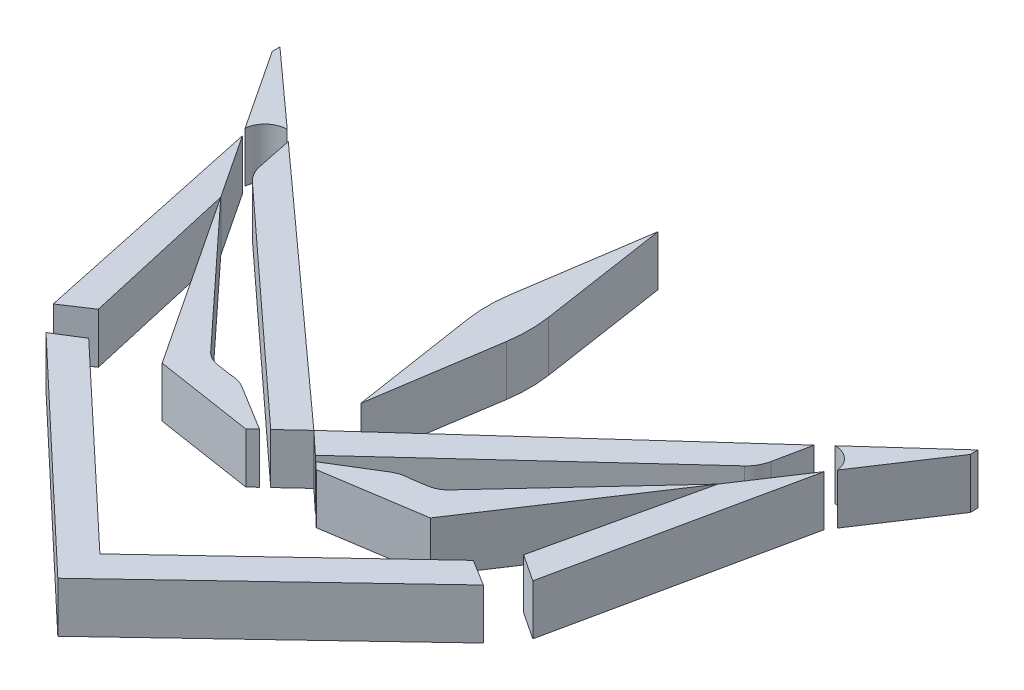
SolidWorks part; units mm, degrees
ref_plane "Front Plane" through (0, 0, 0) normal (0, 0, 1) x (1, 0, 0)
ref_plane "Top Plane" through (0, 0, 0) normal (0, 1, 0) x (1, 0, 0)
ref_plane "Right Plane" through (0, 0, 0) normal (1, 0, 0) x (0, 0, -1)
sketch "Sketch1" plane through (0, 0, 0) normal (0, 1, 0) x (1, 0, 0)
  line L0 (-34.3583, 111.2023) -> (-103.7706, 173.8654)
  line L1 (-103.7706, 173.8654) -> (-103.7706, 172.3321)
  line L2 (-103.7706, 172.3321) -> (-61.0199, 107.7002)
  line L3 (-61.0199, 107.7002) -> (-41.3657, 104.6718)
  line L4 (-41.3657, 104.6718) -> (-34.3583, 111.2023)
  line L5 (-92.2023, 154.8429) -> (-82.0422, 107.0612)
  line L6 (-82.0422, 107.0612) -> (-76.6482, 110.629)
  line L7 (-76.6482, 110.629) -> (-83.7755, 142.103)
  line L8 (-34.3583, 60.2804) -> (-34.3583, 179.6239) construction
  line L9 (-37.1322, 103.8965) -> (-40.9001, 104.4454)
  line L10 (-42.25, 103.8965) -> (-43.2539, 102.5863)
  line L11 (-72.6076, 104.6718) -> (-77.8414, 101.4158)
  line L12 (-77.8414, 101.4158) -> (-34.3583, 60.2804)
  line L13 (-34.3583, 68.6493) -> (-72.6076, 104.6718)
  line L14 (-39.9543, 105.9871) -> (-48.9893, 111.5383)
  line L15 (-52.3282, 112.482) -> (-55.26, 112.9474)
  line L16 (-57.9726, 114.2861) -> (-83.7755, 142.103)
  line L18 (-86.6454, 158.4053) -> (-85.1748, 151.2715)
  line L19 (-83.2991, 147.9149) -> (-38.8018, 107.0612)
  line L20 (-34.3583, 179.6239) -> (-38.2146, 154.0307)
  line L21 (-38.2035, 145.657) -> (-34.3583, 120.5907)
  line L22 (-34.3583, 120.5907) -> (-34.3583, 179.6239)
  line L23 (-43.2539, 102.5863) -> (-37.1322, 103.3967)
  line L24 (-37.1322, 103.3967) -> (-37.1322, 103.8965)
  line L25 (-31.5845, 103.3967) -> (-31.5845, 103.8965)
  line L26 (-25.4628, 102.5863) -> (-31.5845, 103.3967)
  line L27 (-30.5132, 145.657) -> (-34.3583, 120.5907)
  line L28 (-34.3583, 179.6239) -> (-30.502, 154.0307)
  line L29 (14.5824, 147.9149) -> (-29.9148, 107.0612)
  line L30 (17.9287, 158.4053) -> (16.4582, 151.2715)
  line L32 (-10.7441, 114.2861) -> (15.0589, 142.103)
  line L33 (-16.3885, 112.482) -> (-13.4567, 112.9474)
  line L34 (-28.7623, 105.9871) -> (-19.7273, 111.5383)
  line L35 (-34.3583, 68.6493) -> (3.891, 104.6718)
  line L36 (9.1248, 101.4158) -> (-34.3583, 60.2804)
  line L37 (3.891, 104.6718) -> (9.1248, 101.4158)
  line L38 (-26.4666, 103.8965) -> (-25.4628, 102.5863)
  line L39 (-31.5845, 103.8965) -> (-27.8165, 104.4454)
  line L40 (7.9315, 110.629) -> (15.0589, 142.103)
  line L41 (13.3255, 107.0612) -> (7.9315, 110.629)
  line L42 (23.4857, 154.8429) -> (13.3255, 107.0612)
  line L43 (-27.3509, 104.6718) -> (-34.3583, 111.2023)
  line L44 (-7.6968, 107.7002) -> (-27.3509, 104.6718)
  line L45 (35.0539, 172.3321) -> (-7.6968, 107.7002)
  line L46 (35.0539, 173.8654) -> (35.0539, 172.3321)
  line L47 (-34.3583, 111.2023) -> (35.0539, 173.8654)
  arc A0 (-48.9893, 111.5383) -> (-52.3282, 112.482) centre (-52.3282, 106.104) ccw
  arc A1 (-55.26, 112.9474) -> (-57.9726, 114.2861) centre (-54.4603, 117.9855) cw
  arc A2 (-85.1748, 151.2715) -> (-83.2991, 147.9149) centre (-78.9301, 152.5588) ccw
  arc A3 (-88.849, 160.3947) -> (-93.2599, 156.4417) centre (-88.841, 155.9483) ccw
  arc A4 (-38.2146, 154.0307) -> (-38.2035, 145.657) centre (-10.6707, 149.8805) ccw
  arc A5 (-40.9001, 104.4454) -> (-42.25, 103.8965) centre (-41.1076, 103.0211) ccw
  arc A6 (-27.8165, 104.4454) -> (-26.4666, 103.8965) centre (-27.6091, 103.0211) cw
  arc A7 (-30.502, 154.0307) -> (-30.5132, 145.657) centre (-58.0459, 149.8805) cw
  arc A8 (20.1324, 160.3947) -> (24.5432, 156.4417) centre (20.1243, 155.9483) cw
  arc A9 (16.4582, 151.2715) -> (14.5824, 147.9149) centre (10.2135, 152.5588) cw
  arc A10 (-13.4567, 112.9474) -> (-10.7441, 114.2861) centre (-14.2564, 117.9855) ccw
  arc A11 (-19.7273, 111.5383) -> (-16.3885, 112.482) centre (-16.3885, 106.104) cw
  dimension "D1" = 6.378
  dimension "D2" = 5.1012
  dimension "D3" = 6.376
  dimension "D4" = 4.4464
  dimension "D5" = 27.8548
  dimension "D6" = 1.4393
  dimension "D7" = 10.6707
  dimension "D8" = 34.3583
  dimension "D9" = 37.1322
  dimension "D10" = 38.2035
  dimension "D11" = 38.2146
  dimension "D12" = 38.8018
  dimension "D13" = 39.9543
  dimension "D14" = 40.9001
  dimension "D15" = 41.1076
  dimension "D16" = 41.3657
  dimension "D17" = 60.2804
  dimension "D18" = 43.2539
  dimension "D19" = 48.9893
  dimension "D20" = 52.3282
  dimension "D21" = 54.4603
  dimension "D22" = 55.26
  dimension "D23" = 57.9726
  dimension "D24" = 61.0199
  dimension "D25" = 72.6076
  dimension "D26" = 76.6482
  dimension "D27" = 77.8414
  dimension "D28" = 78.9301
  dimension "D29" = 82.0422
  dimension "D30" = 83.2991
  dimension "D31" = 83.7755
  dimension "D32" = 85.1748
  dimension "D33" = 86.6454
  dimension "D34" = 88.841
  dimension "D35" = 88.849
  dimension "D36" = 92.2023
  dimension "D37" = 93.2599
  dimension "D38" = 103.7706
  dimension "D39" = 68.6493
  dimension "D40" = 101.4158
  dimension "D41" = 102.5863
  dimension "D42" = 103.3967
  dimension "D43" = 104.6718
  dimension "D44" = 105.9871
  dimension "D45" = 107.7002
  dimension "D46" = 110.629
  dimension "D47" = 120.5907
extrude "Boss-Extrude1" add sketch "Sketch1" along normal blind 10 contours L18 A2 L19 L4 L0 | A3 L0 L1 L2 | L15 A1 L16 L2 L3 L4 L14 A0 | L6 L7 L2 L5 | L12 L8 L13 L11 | L8 L36 L37 L35 | L42 L45 L40 L41 | L47 A8 L45 L46 | A9 L30 L47 L43 L29 | A11 L34 L43 L44 L45 L32 A10 L33 | A7 L28 L22 L27 | L20 A4 L21 L22
